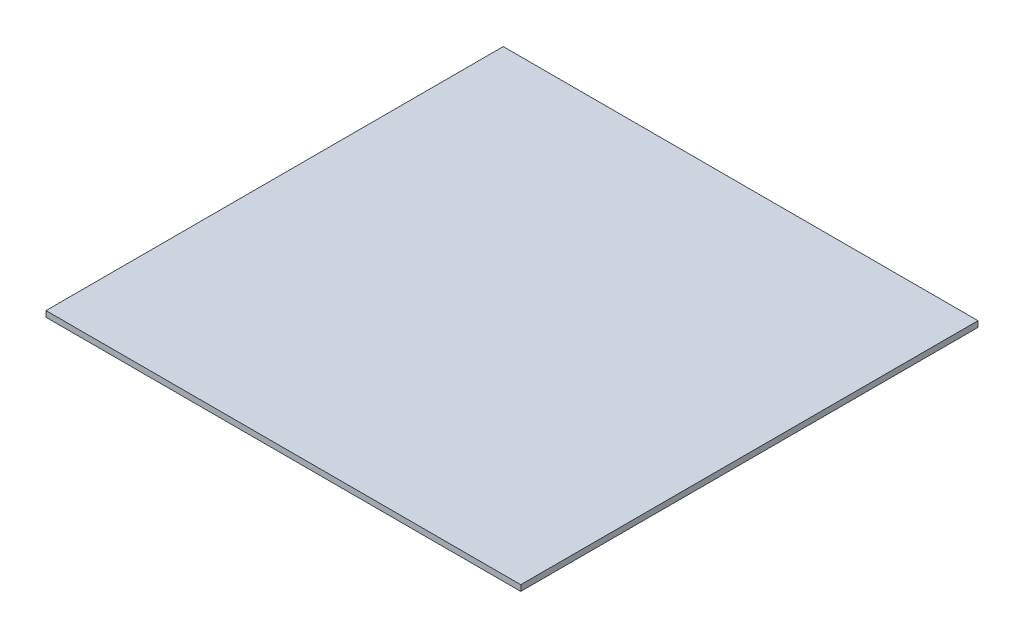
SolidWorks part; units mm, degrees
ref_plane "前视基准面" through (0, 0, 0) normal (0, 0, 1) x (1, 0, 0)
ref_plane "上视基准面" through (0, 0, 0) normal (0, 1, 0) x (1, 0, 0)
ref_plane "右视基准面" through (0, 0, 0) normal (1, 0, 0) x (0, 0, -1)
sketch "草图1" plane through (0, 0, 0) normal (0, 1, 0) x (1, 0, 0)
  line L1 (0, 0) -> (244, 0)
  line L2 (0, 0) -> (0, -235)
  line L3 (0, -235) -> (244, -235)
  line L4 (244, 0) -> (244, -235)
  dimension "D1" = 244
  dimension "D2" = 235
extrude "凸台-拉伸1" add sketch "草图1" along normal blind 3
